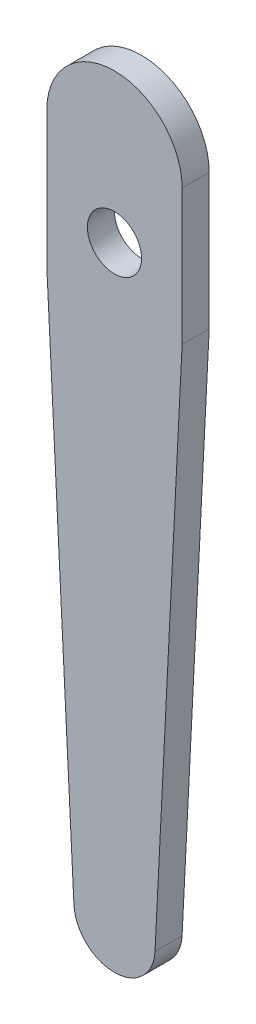
SolidWorks part; units mm, degrees
ref_plane "Front Plane" through (0, 0, 0) normal (0, 0, 1) x (1, 0, 0)
ref_plane "Top Plane" through (0, 0, 0) normal (0, 1, 0) x (1, 0, 0)
ref_plane "Right Plane" through (0, 0, 0) normal (1, 0, 0) x (0, 0, -1)
sketch "Sketch1" plane through (0, 0, 0) normal (0, 0, 1) x (1, 0, 0)
  line L0 (-18.3949, -1638.9741) -> (31.6051, -1638.9741)
  line L1 (31.6051, -1638.9741) -> (31.6051, -1688.9741)
  line L2 (-18.3949, -1638.9741) -> (-18.3949, -1688.9741)
  line L3 (-18.3949, -1688.9741) -> (-8.3759, -1888.2197)
  line L4 (31.6051, -1688.9741) -> (21.5862, -1888.2197)
  circle A0 centre (6.6051, -1887.4664) radius 15
  point P6 (0, 0)
  point P7 (6.6051, -1638.9741)
  point P10 (0, 0)
  point P11 (0, 0)
  point P12 (0, 0)
  dimension "D5" = 30
  dimension "D1" = 50
  dimension "D2" = 50
  dimension "D3" = 50
  dimension "D4" = 5.757
extrude "Boss-Extrude3" add sketch "Sketch1" along normal blind 10 contours A0 | A0 L4 L1 L0 L2 L3
sketch "Sketch2" plane through (0, 0, 0) normal (0, 0, -1) x (-1, 0, 0)
  line L0 (-31.6051, -1638.9741) -> (18.3949, -1638.9741)
  arc A0 (-31.6051, -1638.9741) -> (18.3949, -1638.9741) centre (-6.6051, -1638.9741) cw
extrude "Boss-Extrude4" add sketch "Sketch2" against normal blind 10 contours L0 A0
sketch "Sketch3" plane through (0, 0, 0) normal (0, 0, -1) x (-1, 0, 0)
  circle A0 centre (-6.6051, -1668.9741) radius 10
  arc A1 (18.3949, -1638.9741) -> (-31.6051, -1638.9741) centre (-6.6051, -1638.9741) ccw construction
  point P2 (0, 0)
  point P6 (0, 0)
  point P7 (-6.6051, -1613.9741)
  point P8 (-6.5895, -1670.1846)
  dimension "D1" = 20
  dimension "D2" = 55
extrude "Cut-Extrude1" cut sketch "Sketch3" against normal through all
